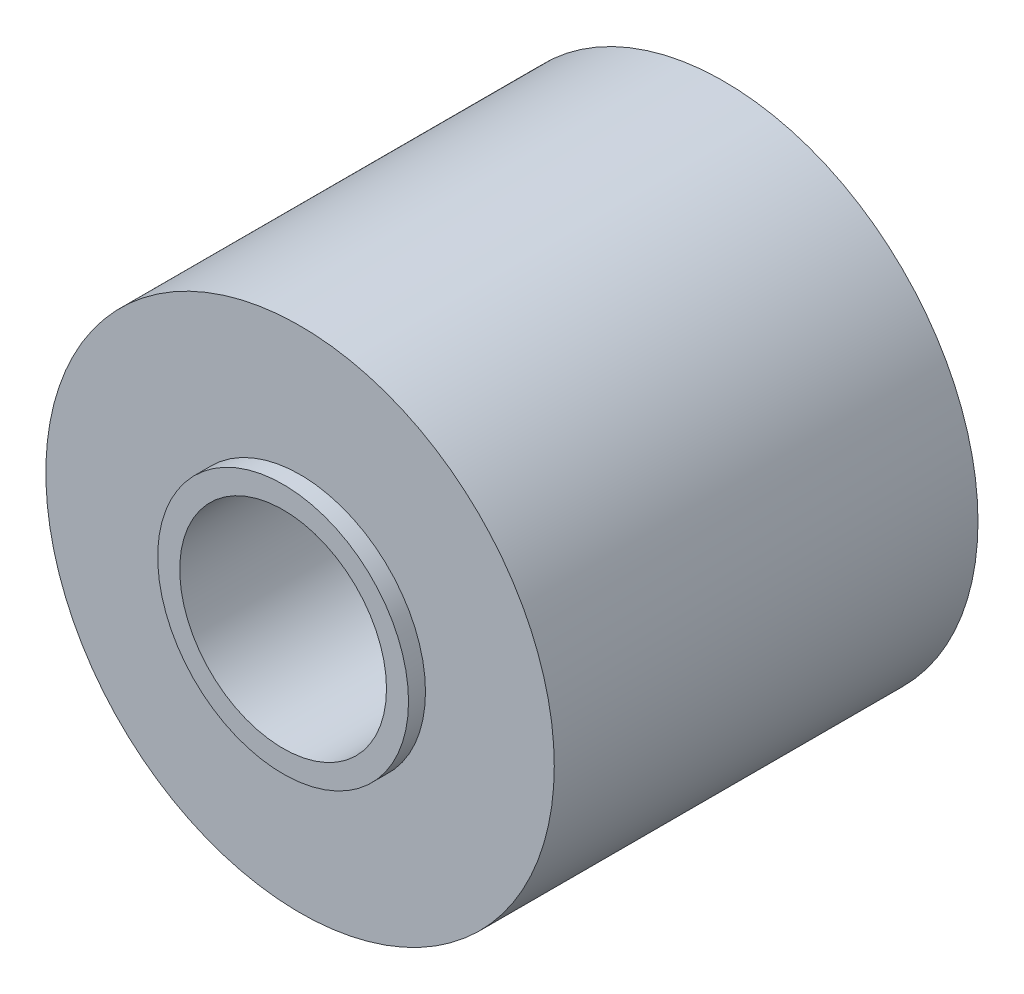
SolidWorks part; units mm, degrees
ref_plane "Front Plane" through (0, 0, 0) normal (0, 0, 1) x (1, 0, 0)
ref_plane "Top Plane" through (0, 0, 0) normal (0, 1, 0) x (1, 0, 0)
ref_plane "Right Plane" through (0, 0, 0) normal (1, 0, 0) x (0, 0, -1)
sketch "Sketch1" plane through (0, 0, 0) normal (0, 0, 1) x (1, 0, 0)
  circle A0 centre (0, 0) radius 7.5
  circle A1 centre (0, 0) radius 3.05
  dimension "D1" = 15
  dimension "D2" = 6.1
extrude "Boss-Extrude1" add sketch "Sketch1" along normal blind 12.5
sketch "Sketch2" plane through (0, 0, 12.5) normal (0, 0, 1) x (1, 0, 0)
  circle A0 centre (0, 0) radius 3.7
  circle A1 centre (0, 0) radius 3.05
  dimension "D1" = 7.4
  dimension "D2" = 6.1
extrude "Boss-Extrude2" add sketch "Sketch2" along direction (0, 0, 1) on the side of the normal blind 0.5
